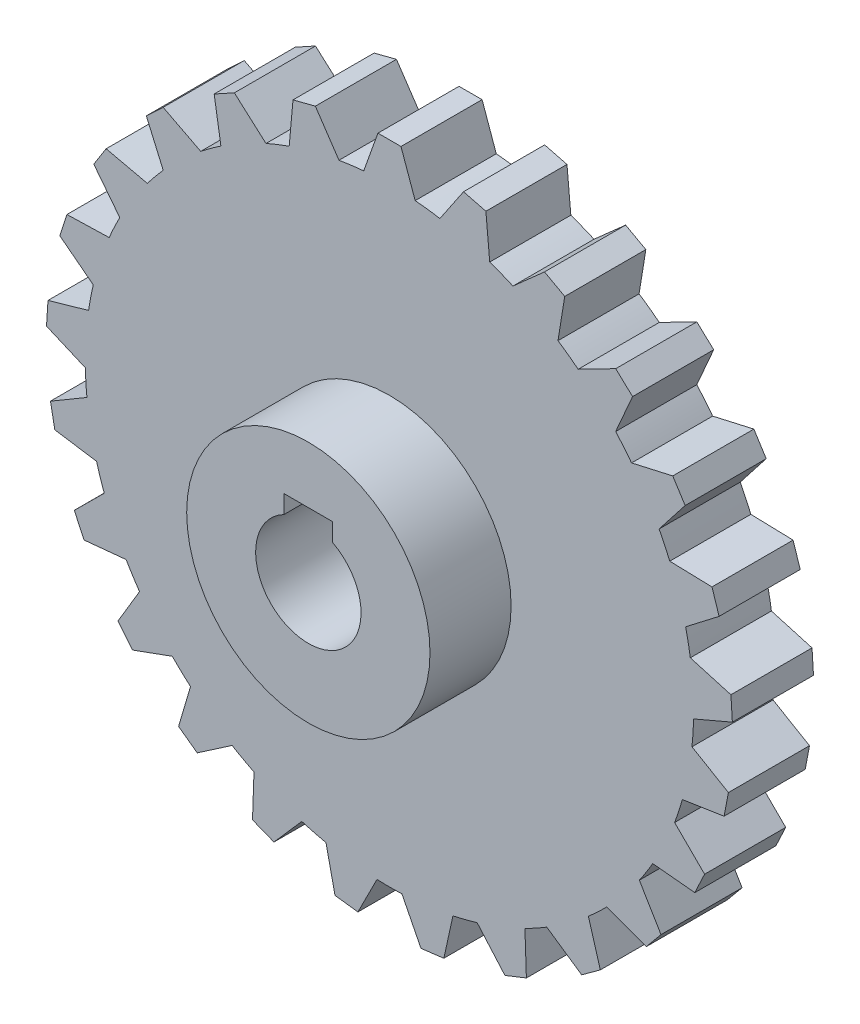
SolidWorks part; units mm, degrees
ref_plane "Front Plane" through (0, 0, 0) normal (0, 0, 1) x (1, 0, 0)
ref_plane "Top Plane" through (0, 0, 0) normal (0, 1, 0) x (1, 0, 0)
ref_plane "Right Plane" through (0, 0, 0) normal (1, 0, 0) x (0, 0, -1)
sketch "Sketch1" plane through (0, 0, 0) normal (0, 0, 1) x (1, 0, 0)
  line L0 (0, 0) -> (0, 140.563) construction
  line L2 (6.3398, 74.7316) -> (2.8434, 84.5496)
  line L3 (-6.3398, 74.7316) -> (-2.8434, 84.5496)
  line L4 (-2.8434, 84.5496) -> (2.8434, 84.5496)
  line L5 (24.7256, 70.8071) -> (23.7807, 81.1862)
  line L6 (18.2726, 82.6004) -> (23.7807, 81.1862)
  line L7 (12.4444, 73.9604) -> (18.2726, 82.6004)
  line L8 (41.5578, 62.4336) -> (43.2237, 72.7215)
  line L9 (38.2404, 75.4611) -> (43.2237, 72.7215)
  line L10 (30.4466, 68.542) -> (38.2404, 75.4611)
  line L11 (55.7788, 50.1371) -> (59.9509, 59.6876)
  line L12 (55.8054, 63.5804) -> (59.9509, 59.6876)
  line L13 (46.5358, 58.8168) -> (55.8054, 63.5804)
  line L14 (66.495, 34.6903) -> (72.9111, 42.9032)
  line L15 (69.864, 47.7047) -> (72.9111, 42.9032)
  line L16 (59.7009, 45.396) -> (69.864, 47.7047)
  line L17 (73.033, 17.0639) -> (81.2901, 23.423)
  line L18 (79.5328, 28.8315) -> (81.2901, 23.423)
  line L19 (69.1149, 29.1228) -> (79.5328, 28.8315)
  line L20 (74.9822, -1.6348) -> (84.5613, 2.4712)
  line L21 (84.2042, 8.1467) -> (84.5613, 2.4712)
  line L22 (74.186, 11.0197) -> (84.2042, 8.1467)
  line L23 (72.2199, -20.2308) -> (82.5192, -18.636)
  line L24 (83.5847, -13.05) -> (82.5192, -18.636)
  line L25 (74.5958, -7.7758) -> (83.5847, -13.05)
  line L26 (64.9198, -37.5555) -> (75.2921, -38.5722)
  line L27 (77.7134, -33.4267) -> (75.2921, -38.5722)
  line L28 (70.3185, -26.0828) -> (77.7134, -33.4267)
  line L29 (53.5406, -52.5206) -> (63.3341, -56.0848)
  line L30 (66.959, -51.7031) -> (63.3341, -56.0848)
  line L31 (61.6228, -42.7508) -> (66.959, -51.7031)
  line L32 (38.7971, -64.1855) -> (47.3966, -70.0733)
  line L33 (51.9973, -66.7307) -> (47.3966, -70.0733)
  line L34 (49.0551, -56.7327) -> (51.9973, -66.7307)
  line L35 (21.616, -71.8175) -> (28.4811, -79.6589)
  line L36 (33.7685, -77.5655) -> (28.4811, -79.6589)
  line L37 (33.4051, -67.1498) -> (33.7685, -77.5655)
  line L38 (3.0766, -74.9369) -> (7.7759, -84.2392)
  line L39 (13.4178, -83.5265) -> (7.7759, -84.2392)
  line L40 (15.6561, -73.3477) -> (13.4178, -83.5265)
  line L41 (-15.6561, -73.3477) -> (-13.4178, -83.5265)
  line L42 (-7.7759, -84.2392) -> (-13.4178, -83.5265)
  line L43 (-3.0766, -74.9369) -> (-7.7759, -84.2392)
  line L44 (-33.4051, -67.1498) -> (-33.7685, -77.5655)
  line L45 (-28.4811, -79.6589) -> (-33.7685, -77.5655)
  line L46 (-21.616, -71.8175) -> (-28.4811, -79.6589)
  line L47 (-49.0551, -56.7327) -> (-51.9973, -66.7307)
  line L48 (-47.3966, -70.0733) -> (-51.9973, -66.7307)
  line L49 (-38.7971, -64.1855) -> (-47.3966, -70.0733)
  line L50 (-61.6228, -42.7508) -> (-66.959, -51.7031)
  line L51 (-63.3341, -56.0848) -> (-66.959, -51.7031)
  line L52 (-53.5406, -52.5206) -> (-63.3341, -56.0848)
  line L53 (-70.3185, -26.0828) -> (-77.7134, -33.4267)
  line L54 (-75.2921, -38.5722) -> (-77.7134, -33.4267)
  line L55 (-64.9198, -37.5555) -> (-75.2921, -38.5722)
  line L56 (-74.5958, -7.7758) -> (-83.5847, -13.05)
  line L57 (-82.5192, -18.636) -> (-83.5847, -13.05)
  line L58 (-72.2199, -20.2308) -> (-82.5192, -18.636)
  line L59 (-74.186, 11.0197) -> (-84.2042, 8.1467)
  line L60 (-84.5613, 2.4712) -> (-84.2042, 8.1467)
  line L61 (-74.9822, -1.6348) -> (-84.5613, 2.4712)
  line L62 (-69.1149, 29.1228) -> (-79.5328, 28.8315)
  line L63 (-81.2901, 23.423) -> (-79.5328, 28.8315)
  line L64 (-73.033, 17.0639) -> (-81.2901, 23.423)
  line L65 (-59.7009, 45.396) -> (-69.864, 47.7047)
  line L66 (-72.9111, 42.9032) -> (-69.864, 47.7047)
  line L67 (-66.495, 34.6903) -> (-72.9111, 42.9032)
  line L68 (-46.5358, 58.8168) -> (-55.8054, 63.5804)
  line L69 (-59.9509, 59.6876) -> (-55.8054, 63.5804)
  line L70 (-55.7788, 50.1371) -> (-59.9509, 59.6876)
  line L71 (-30.4466, 68.542) -> (-38.2404, 75.4611)
  line L72 (-43.2237, 72.7215) -> (-38.2404, 75.4611)
  line L73 (-41.5578, 62.4336) -> (-43.2237, 72.7215)
  line L74 (-12.4444, 73.9604) -> (-18.2726, 82.6004)
  line L75 (-23.7807, 81.1862) -> (-18.2726, 82.6004)
  line L76 (-24.7256, 70.8071) -> (-23.7807, 81.1862)
  arc A0 (-6.3398, 74.7316) -> (-12.4444, 73.9604) centre (0, 0) ccw
  arc A1 (-24.7256, 70.8071) -> (-30.4466, 68.542) centre (0, 0) ccw
  arc A2 (-41.5578, 62.4336) -> (-46.5358, 58.8168) centre (0, 0) ccw
  arc A3 (-55.7788, 50.1371) -> (-59.7009, 45.396) centre (0, 0) ccw
  arc A4 (-66.495, 34.6903) -> (-69.1149, 29.1228) centre (0, 0) ccw
  arc A5 (-73.033, 17.0639) -> (-74.186, 11.0197) centre (0, 0) ccw
  arc A6 (-74.9822, -1.6348) -> (-74.5958, -7.7758) centre (0, 0) ccw
  arc A7 (-72.2199, -20.2308) -> (-70.3185, -26.0828) centre (0, 0) ccw
  arc A8 (-64.9198, -37.5555) -> (-61.6228, -42.7508) centre (0, 0) ccw
  arc A9 (-53.5406, -52.5206) -> (-49.0551, -56.7327) centre (0, 0) ccw
  arc A10 (-38.7971, -64.1855) -> (-33.4051, -67.1498) centre (0, 0) ccw
  arc A11 (-21.616, -71.8175) -> (-15.6561, -73.3477) centre (0, 0) ccw
  arc A12 (15.6561, -73.3477) -> (21.616, -71.8175) centre (0, 0) ccw
  arc A13 (30.4466, 68.542) -> (24.7256, 70.8071) centre (0, 0) ccw
  arc A14 (46.5358, 58.8168) -> (41.5578, 62.4336) centre (0, 0) ccw
  arc A15 (59.7009, 45.396) -> (55.7788, 50.1371) centre (0, 0) ccw
  arc A16 (69.1149, 29.1228) -> (66.495, 34.6903) centre (0, 0) ccw
  arc A17 (74.186, 11.0197) -> (73.033, 17.0639) centre (0, 0) ccw
  arc A18 (74.5958, -7.7758) -> (74.9822, -1.6348) centre (0, 0) ccw
  arc A19 (70.3185, -26.0828) -> (72.2199, -20.2308) centre (0, 0) ccw
  arc A20 (61.6228, -42.7508) -> (64.9198, -37.5555) centre (0, 0) ccw
  arc A21 (49.0551, -56.7327) -> (53.5406, -52.5206) centre (0, 0) ccw
  arc A22 (33.4051, -67.1498) -> (38.7971, -64.1855) centre (0, 0) ccw
  arc A23 (-3.0766, -74.9369) -> (3.0766, -74.9369) centre (0, 0) ccw
  arc A24 (12.4444, 73.9604) -> (6.3398, 74.7316) centre (0, 0) ccw
  point P7 (0, 75)
  point P107 (0, 0)
  dimension "D1" = 150
  dimension "D2" = 25
extrude "Boss-Extrude1" add sketch "Sketch1" along normal blind 20
sketch "Sketch3" plane through (0, 0, 20) normal (0, 0, 1) x (1, 0, 0)
  circle A0 centre (0, 0) radius 30
  dimension "D1" = 60
extrude "Boss-Extrude2" add sketch "Sketch3" along normal blind 20
sketch "Sketch4" plane through (0, 0, 40) normal (0, 0, 1) x (1, 0, 0)
  line L0 (0, 0) -> (0, 10) construction
  line L1 (0, 13) -> (0, 43.8596) construction
  line L2 (-6, 16) -> (6, 16)
  line L3 (-6, 16) -> (-6, 11.5326)
  line L5 (6, 16) -> (6, 11.5326)
  line L6 (-6, 16) -> (0, 13) construction
  line L7 (0, 13) -> (6, 16) construction
  arc A0 (-6, 11.5326) -> (6, 11.5326) centre (0, 0) ccw
  point P3 (0, 13)
  dimension "D1" = 26
  dimension "D2" = 12
  dimension "D3" = 12
  dimension "D4" = 4.4674
extrude "Cut-Extrude1" cut sketch "Sketch4" against normal through all
